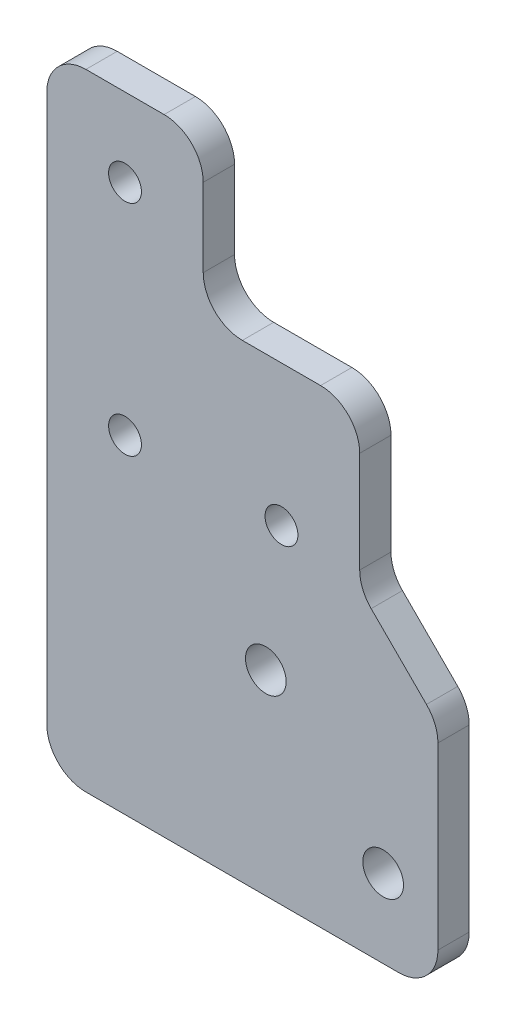
SolidWorks part; units mm, degrees
ref_plane "Спереди" through (0, 0, 0) normal (0, 0, 1) x (1, 0, 0)
ref_plane "Сверху" through (0, 0, 0) normal (0, 1, 0) x (1, 0, 0)
ref_plane "Справа" through (0, 0, 0) normal (1, 0, 0) x (0, 0, -1)
sketch "Model" plane through (0, 0, 0) normal (0, 0, 1) x (1, 0, 0)
  line L92 (308.3927, 233.3937) -> (308.3927, 210.4648)
  line L93 (303.3927, 205.4648) -> (263.3927, 205.4648)
  line L94 (258.3928, 210.4648) -> (258.3928, 280.4647)
  line L95 (263.3927, 285.4647) -> (273.3927, 285.4647)
  line L96 (278.3927, 280.4647) -> (278.3927, 270.4647)
  line L97 (283.3927, 265.4647) -> (293.3927, 265.4647)
  line L98 (298.3927, 260.4647) -> (298.3927, 247.5358)
  line L99 (299.8571, 244.0003) -> (306.9282, 236.9292)
  circle A59 centre (286.3927, 230.4648) radius 2.6
  circle A60 centre (301.3927, 215.4648) radius 2.6
  circle A61 centre (268.3927, 275.4647) radius 2.1
  circle A62 centre (268.3927, 247.4648) radius 2.1
  circle A63 centre (288.3927, 247.4648) radius 2.1
  arc A173 (303.3927, 205.4648) -> (308.3927, 210.4648) centre (303.3927, 210.4648) ccw
  arc A174 (258.3928, 210.4648) -> (263.3927, 205.4648) centre (263.3927, 210.4648) ccw
  arc A175 (263.3927, 285.4647) -> (258.3928, 280.4647) centre (263.3927, 280.4647) ccw
  arc A176 (278.3927, 280.4647) -> (273.3927, 285.4647) centre (273.3927, 280.4647) ccw
  arc A177 (278.3927, 270.4647) -> (283.3927, 265.4647) centre (283.3927, 270.4647) ccw
  arc A178 (298.3927, 260.4647) -> (293.3927, 265.4647) centre (293.3927, 260.4647) ccw
  arc A179 (298.3927, 247.5358) -> (299.8571, 244.0003) centre (303.3927, 247.5358) ccw
  arc A180 (308.3927, 233.3937) -> (306.9282, 236.9292) centre (303.3927, 233.3937) ccw
extrude "Бобышка-Вытянуть1" add sketch "Model" along normal blind 4
